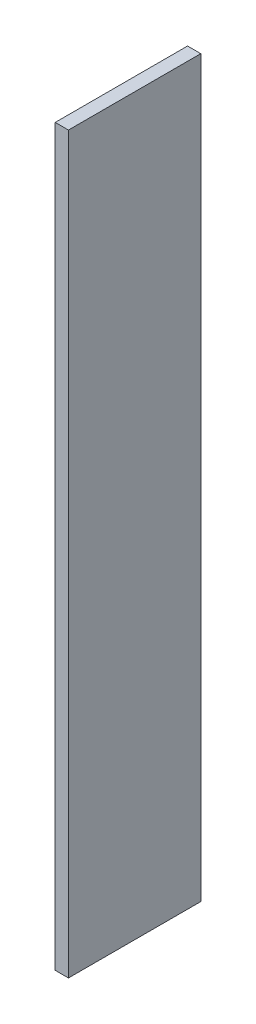
SolidWorks part; units mm, degrees
ref_plane "Front Plane" through (0, 0, 0) normal (0, 0, 1) x (1, 0, 0)
ref_plane "Top Plane" through (0, 0, 0) normal (0, 1, 0) x (1, 0, 0)
ref_plane "Right Plane" through (0, 0, 0) normal (1, 0, 0) x (0, 0, -1)
sketch "Sketch1" plane through (0, 0, 0) normal (1, 0, 0) x (0, 0, -1)
  line L1 (-10, -55.5) -> (10, -55.5)
  line L2 (-10, -55.5) -> (-10, 55.5)
  line L3 (-10, 55.5) -> (10, 55.5)
  line L4 (10, -55.5) -> (10, 55.5)
  line L5 (-10, -55.5) -> (10, 55.5) construction
  line L6 (-10, 55.5) -> (10, -55.5) construction
  point P0 (0, 0)
  dimension "D1" = 20
  dimension "D2" = 111
extrude "Boss-Extrude1" add sketch "Sketch1" along normal mid plane 2
